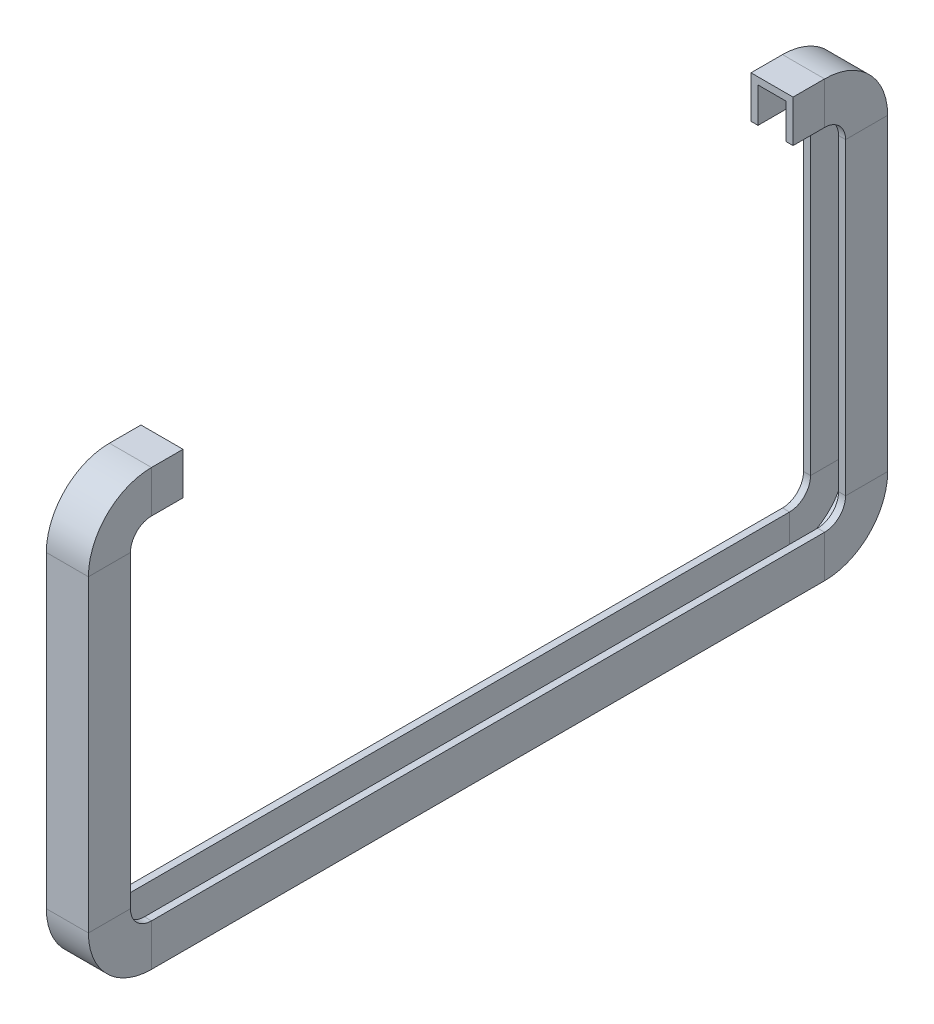
SolidWorks part; units mm, degrees
ref_plane "Front Plane" through (0, 0, 0) normal (0, 0, 1) x (1, 0, 0)
ref_plane "Top Plane" through (0, 0, 0) normal (0, 1, 0) x (1, 0, 0)
ref_plane "Right Plane" through (0, 0, 0) normal (1, 0, 0) x (0, 0, -1)
sketch "Sketch2" plane through (0, 0, 0) normal (0, 0, 1) x (1, 0, 0)
  line L0 (0, 0) -> (6.35, 0)
  line L1 (6.35, 0) -> (6.35, -7.9375)
  line L2 (6.35, -7.9375) -> (7.9375, -7.9375)
  line L3 (7.9375, -7.9375) -> (7.9375, 1.5875)
  line L4 (7.9375, 1.5875) -> (-1.5875, 1.5875)
  line L5 (-1.5875, 1.5875) -> (-1.5875, -7.9375)
  line L6 (-1.5875, -7.9375) -> (0, -7.9375)
  line L7 (0, -7.9375) -> (0, 0)
  dimension "D1" = 6.35
  dimension "D2" = 9.525
  dimension "D3" = 7.9375
  dimension "D4" = 9.525
sketch "Sketch3" plane through (0, 0, 0) normal (1, 0, 0) x (0, 0, -1)
  line L0 (0, 0) -> (-7.1374, 0)
  line L1 (-19.8374, -12.7) -> (-19.8374, -82.55)
  line L2 (-7.1374, -95.25) -> (145.2626, -95.25)
  line L3 (157.9626, -82.55) -> (157.9626, -12.7)
  line L4 (145.2626, 0) -> (138.1252, 0)
  arc A0 (-19.8374, -12.7) -> (-7.1374, 0) centre (-7.1374, -12.7) cw
  arc A1 (-7.1374, -95.25) -> (-19.8374, -82.55) centre (-7.1374, -82.55) cw
  arc A2 (157.9626, -82.55) -> (145.2626, -95.25) centre (145.2626, -82.55) cw
  arc A3 (145.2626, 0) -> (157.9626, -12.7) centre (145.2626, -12.7) cw
  point P9 (-19.8374, 0)
  dimension "D2" = 12.7
  dimension "D1" = 19.8374
  dimension "D6" = 177.8
  dimension "D7" = 95.25
sweep "Sweep3" add profiles "Sketch2" path "Sketch3"
